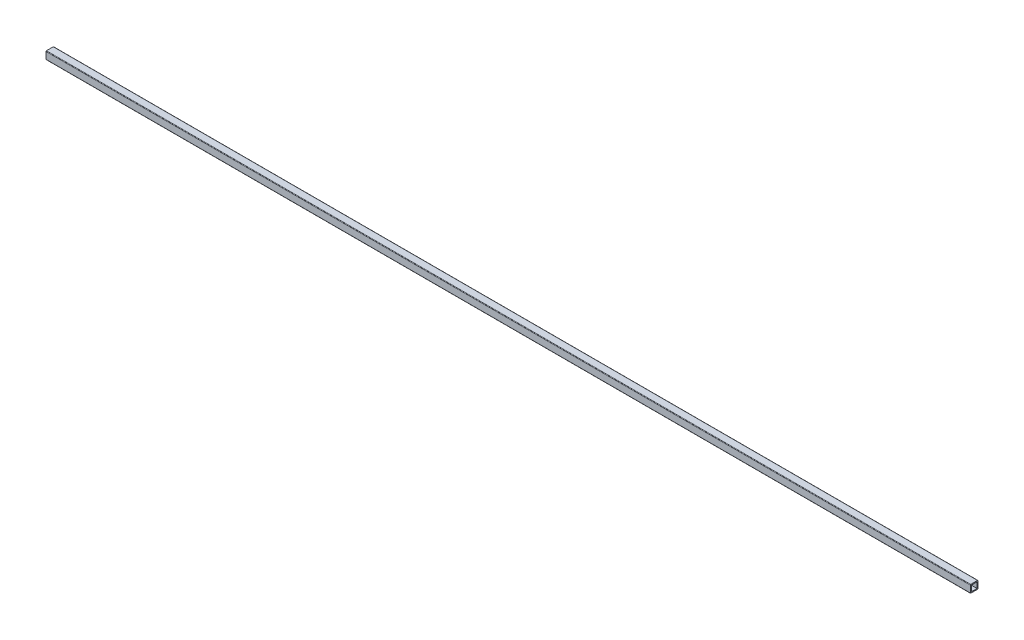
SolidWorks part; units mm, degrees
ref_plane "Front Plane" through (0, 0, 0) normal (0, 0, 1) x (1, 0, 0)
ref_plane "Top Plane" through (0, 0, 0) normal (0, 1, 0) x (1, 0, 0)
ref_plane "Right Plane" through (0, 0, 0) normal (1, 0, 0) x (0, 0, -1)
sketch "Sketch1" plane through (0, 0, 0) normal (0, 0, 1) x (1, 0, 0)
  line L0 (0, 0) -> (1524, 0)
  dimension "D1" = 1524
other "Structural Member1"
ref_plane "Plane1" through (0, 0, 0) normal (1, 0, 0) x (0, 1, 0)
sketch "Sketch11" plane through (0, 0, 0) normal (1, 0, 0) x (0, 1, 0)
  line L0 (-6.35, -6.35) -> (6.35, 6.35) construction
  line L1 (-5.5562, 6.35) -> (5.5562, 6.35)
  line L2 (-6.35, 5.5562) -> (-6.35, -5.5562)
  line L3 (-5.5562, -6.35) -> (5.5562, -6.35)
  line L4 (6.35, 5.5562) -> (6.35, -5.5562)
  line L5 (-4.699, 4.699) -> (-4.699, -4.699)
  line L6 (-4.699, -4.699) -> (4.699, -4.699)
  line L7 (4.699, 4.699) -> (4.699, -4.699)
  line L8 (-4.699, 4.699) -> (4.699, 4.699)
  line L9 (0, 0) -> (6.35, -6.35) construction
  line L10 (6.35, -6.35) -> (-6.35, 6.35) construction
  arc A0 (-6.35, -5.5562) -> (-5.5562, -6.35) centre (-5.5562, -5.5562) ccw
  arc A1 (5.5562, -6.35) -> (6.35, -5.5562) centre (5.5563, -5.5562) ccw
  arc A2 (5.5562, 6.35) -> (6.35, 5.5562) centre (5.5563, 5.5563) cw
  arc A3 (-5.5562, 6.35) -> (-6.35, 5.5562) centre (-5.5562, 5.5563) ccw
  arc A4 (-4.699, -4.699) -> (-4.699, -4.699) centre (-4.699, -4.699) ccw
  arc A5 (4.699, -4.699) -> (4.699, -4.699) centre (4.699, -4.699) ccw
  arc A6 (4.699, 4.699) -> (4.699, 4.699) centre (4.699, 4.699) cw
  arc A7 (-4.699, 4.699) -> (-4.699, 4.699) centre (-4.699, 4.699) ccw
  point P11 (6.35, -6.35)
  point P17 (-6.35, 6.35)
  point P18 (-6.35, 0.5988)
  point P19 (0, 6.35)
  point P20 (6.35, 0)
  point P21 (0, -6.35)
  point P35 (0, 0)
  dimension "D3" = 0.7937
  dimension "D1" = 12.7
  dimension "D2" = 12.7
  dimension "D4" = 1.651
